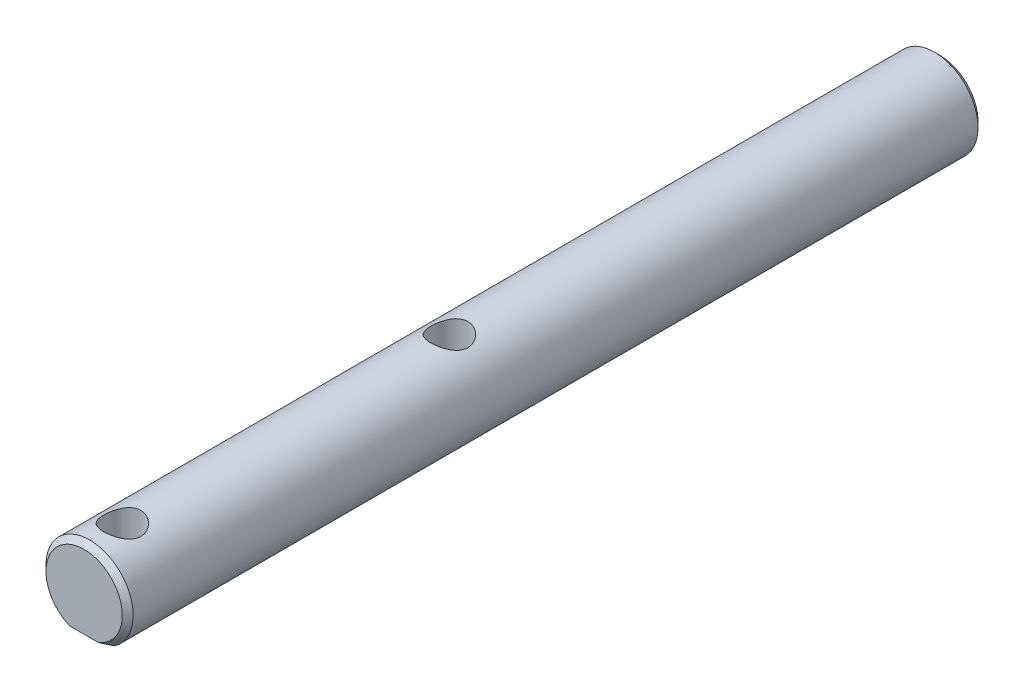
SolidWorks part; units mm, degrees
ref_plane "Front Plane" through (0, 0, 0) normal (0, 0, 1) x (1, 0, 0)
ref_plane "Top Plane" through (0, 0, 0) normal (0, 1, 0) x (1, 0, 0)
ref_plane "Right Plane" through (0, 0, 0) normal (1, 0, 0) x (0, 0, -1)
sketch "Sketch1" plane through (0, 0, 0) normal (0, 0, 1) x (1, 0, 0)
  line L2 (-6.9282, -29.5025) -> (6.9282, -29.5025) construction
  arc A0 (6.9282, -29.5025) -> (-6.9282, -29.5025) centre (0, -25.5025) ccw
  arc A1 (6.9282, -29.5025) -> (-6.9282, -29.5025) centre (0, -25.5025) cw
  point P8 (0, -34.8025)
  dimension "D1" = 4
  dimension "D2" = 8
extrude "Boss-Extrude1" add sketch "Sketch1" along normal blind 32 and the other way blind 125
sketch "Sketch2" plane through (0, 0, 32) normal (0, 0, 1) x (1, 0, 0)
  line L1 (-4.6637, -32.0025) -> (4.6637, -32.0025)
  circle A0 centre (0, -25.5025) radius 8 construction
  arc A1 (-4.6637, -32.0025) -> (4.6637, -32.0025) centre (0, -25.5025) ccw
  dimension "D1" = 6.5
extrude "Cut-Extrude1" cut sketch "Sketch2" against normal blind 15
ref_plane "Plane1" through (0, 0, -43) normal (0, 0, 1) x (1, 0, 0)
sketch "Sketch3" plane through (0, 0, -43) normal (0, 0, 1) x (1, 0, 0)
  line L0 (4.6637, -32.0025) -> (-4.6637, -32.0025) construction
  line L2 (4.6637, -32.0025) -> (-4.6637, -32.0025)
  arc A0 (-4.6637, -32.0025) -> (4.6637, -32.0025) centre (0, -25.5025) ccw construction
  arc A2 (-4.6637, -32.0025) -> (4.6637, -32.0025) centre (0, -25.5025) ccw
extrude "Cut-Extrude2" cut sketch "Sketch3" along normal blind 16
sketch "Sketch4" plane through (0, -32.0025, 0) normal (0, 1, 0) x (1, 0, 0)
  circle A3 centre (0, -25) radius 3 construction
  circle A5 centre (0, -25) radius 3.1 construction
  circle A6 centre (0, -25) radius 2.5
  dimension "D3" = 5
hole_wizard "M8 Tapped Hole1" positions "Sketch5" profile "Sketch6" tap size "M8" standard "DIN"
sketch "Sketch5" plane through (0, 0, -125) normal (0, 0, -1) x (-1, 0, 0)
  point P0 (0, -25.5025)
sketch "Sketch6" plane through (0, -25.5025, -125) normal (1, 0, 0) x (0, 1, 0)
  line L0 (0, 0) -> (0, 42.0429)
  line L1 (0, 42.0429) -> (3.4, 40)
  line L2 (3.4, 40) -> (3.4, 0)
  line L5 (3.4, 0) -> (0, 0)
  line L10 (0, 42.0429) -> (-3.4, 40) construction
  line L11 (0, -6.35) -> (0, 107.95) construction
  dimension "Tap Drill Dia." = 6.8
  dimension "Tap Drill Depth" = 40
  dimension "Drill Angle" = 118
cosmetic thread "Hole Thread1" parameters "D1"=38, "D2"=8
chamfer "Chamfer1" distance 1 angle 45 1 edges at (-8, -25.5025, -125)
chamfer "Chamfer2" distance 1 angle 45 1 edges at (0, -17.5025, 32)
hole_wizard "M8 Tapped Hole2" positions "Sketch7" profile "Sketch8" tap size "M8" standard "ISO" end condition through all
sketch "Sketch7" plane through (0, -32.0025, 0) normal (0, -1, 0) x (-1, 0, 0)
  point P0 (0, -25)
  point P3 (0, 35)
  point P6 (0, 0)
  dimension "D1" = 60
sketch "Sketch8" plane through (0, -32.0025, 25) normal (1, 0, 0) x (0, 0, -1)
  line L0 (0, 0) -> (0, 14.5)
  line L1 (0, 14.5) -> (3.4, 14.5)
  line L2 (3.4, 14.5) -> (3.4, 0)
  line L5 (3.4, 0) -> (0, 0)
  line L11 (0, -6.35) -> (0, 107.95) construction
  dimension "Thru Tap Drill Dia." = 6.8
  dimension "Thru Tap Drill Depth" = 14.5
cosmetic thread "Hole Thread2" parameters "D2"=8
cosmetic thread "Hole Thread3" parameters "D2"=8
